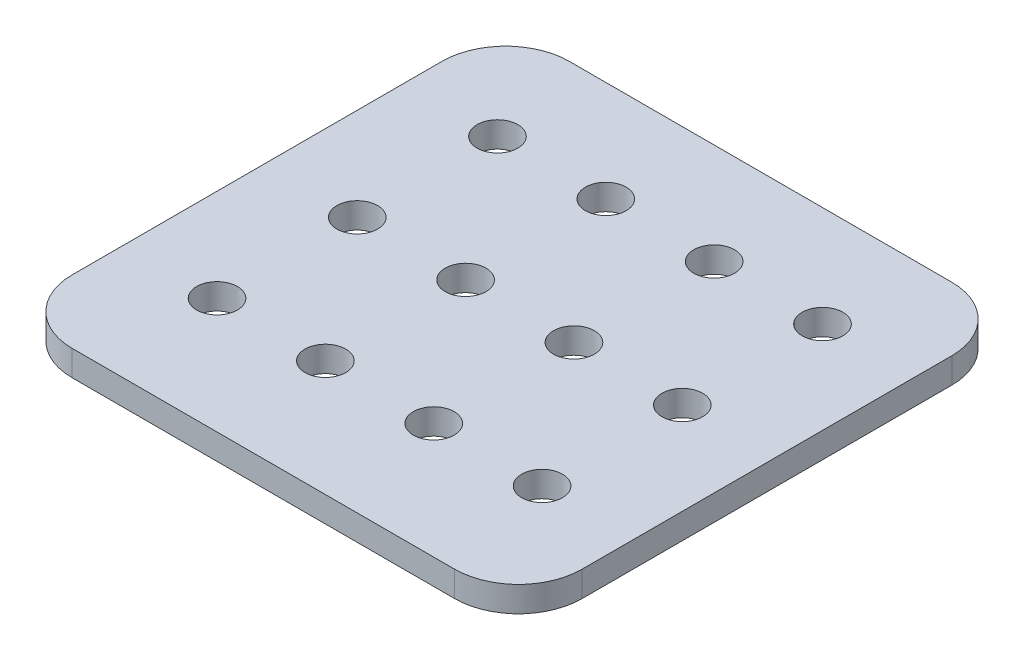
SolidWorks part; units mm, degrees
ref_plane "Front Plane" through (0, 0, 0) normal (0, 0, 1) x (1, 0, 0)
ref_plane "Top Plane" through (0, 0, 0) normal (0, 1, 0) x (1, 0, 0)
ref_plane "Right Plane" through (0, 0, 0) normal (1, 0, 0) x (0, 0, -1)
sketch "Sketch1" plane through (0, 0, 0) normal (0, 1, 0) x (1, 0, 0)
  line L0 (-47.2203, 25.1599) -> (-7.2203, 25.1599)
  line L1 (-7.2203, 25.1599) -> (-7.2203, -13.8401)
  line L2 (-7.2203, -13.8401) -> (-47.2203, -13.8401)
  line L3 (-47.2203, -13.8401) -> (-47.2203, 25.1599)
  line L4 (-27.2203, 25.1599) -> (-27.2203, -13.8401) construction
  line L5 (-47.2203, 5.6599) -> (-7.2203, 5.6599) construction
  circle A0 centre (-14.4457, 17.2452) radius 1.6
  circle A1 centre (-14.4457, 6.2452) radius 1.6
  circle A2 centre (-14.4457, -4.7548) radius 1.6
  circle A3 centre (-22.9457, 17.2452) radius 1.6
  circle A4 centre (-22.9457, 6.2452) radius 1.6
  circle A5 centre (-22.9457, -4.7548) radius 1.6
  circle A6 centre (-31.4457, 17.2452) radius 1.6
  circle A7 centre (-31.4457, 6.2452) radius 1.6
  circle A8 centre (-31.4457, -4.7548) radius 1.6
  circle A9 centre (-39.9457, 17.2452) radius 1.6
  circle A10 centre (-39.9457, 6.2452) radius 1.6
  circle A11 centre (-39.9457, -4.7548) radius 1.6
  point P36 (0, 0)
  dimension "D5" = 3.2
  dimension "D1" = 39
  dimension "D2" = 40
  dimension "D3" = 25.1599
  dimension "D4" = 47.2203
  dimension "D6" = 8.5
  dimension "D7" = 8.5
  dimension "D8" = 8.5
  dimension "D9" = 8.5
  dimension "D10" = 8.5
  dimension "D11" = 8.5
  dimension "D12" = 8.5
  dimension "D13" = 8.5
  dimension "D14" = 8.5
extrude "Boss-Extrude1" add sketch "Sketch1" along normal blind 2
fillet "Fillet1" radius 5 4 edges at (-7.2203, 1, -25.1599) (-7.2203, 1, 13.8401) (-47.2203, 1, -25.1599) (-47.2203, 1, 13.8401)
